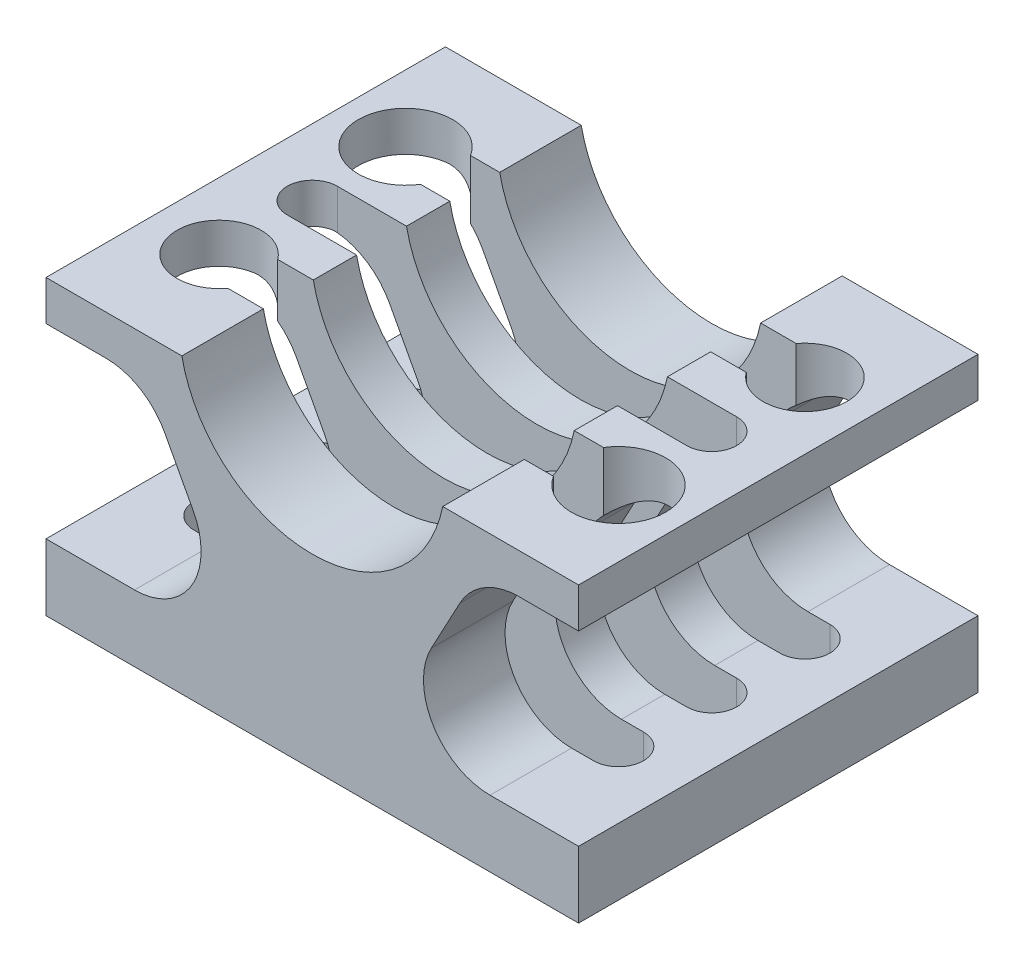
SolidWorks part; units mm, degrees
ref_plane "Front Plane" through (0, 0, 0) normal (0, 0, 1) x (1, 0, 0)
ref_plane "Top Plane" through (0, 0, 0) normal (0, 1, 0) x (1, 0, 0)
ref_plane "Right Plane" through (0, 0, 0) normal (1, 0, 0) x (0, 0, -1)
sketch "Sketch1" plane through (0, 0, 0) normal (0, 0, 1) x (1, 0, 0)
  line L0 (38.1, 30.48) -> (50.8, 30.48)
  line L1 (0, 0) -> (50.8, 0)
  line L2 (0, 0) -> (0, 6.35)
  line L3 (0, 30.48) -> (12.7, 30.48)
  line L4 (50.8, 0) -> (50.8, 6.35)
  line L5 (0, 24.13) -> (0, 30.48)
  line L6 (0, 24.13) -> (9.525, 24.13)
  line L8 (0, 6.35) -> (19.05, 6.35)
  line L9 (9.525, 24.13) -> (19.05, 6.35)
  line L10 (50.8, 24.13) -> (50.8, 30.48)
  line L11 (50.8, 24.13) -> (41.275, 24.13)
  line L13 (50.8, 6.35) -> (31.75, 6.35)
  line L14 (41.275, 24.13) -> (31.75, 6.35)
  arc A0 (12.7, 30.48) -> (38.1, 30.48) centre (25.4, 30.48) ccw
  dimension "D1" = 12.7
  dimension "D2" = 12.7
  dimension "D3" = 12.7
  dimension "D4" = 30.48
  dimension "D5" = 9.525
  dimension "D6" = 6.35
  dimension "D7" = 6.35
  dimension "D8" = 19.05
extrude "Boss-Extrude1" add sketch "Sketch1" along normal blind 38.1
sketch "Sketch3" plane through (0, 0, 0) normal (0, -1, 0) x (1, 0, 0)
  line L0 (6.35, 21.4313) -> (44.45, 21.4312)
  line L1 (6.35, 16.6687) -> (44.45, 16.6688)
  line L2 (0, 38.1) -> (0, 0) construction
  line L3 (6.35, 30.3213) -> (44.45, 30.3213)
  line L4 (6.35, 25.5587) -> (44.45, 25.5587)
  line L5 (6.35, 12.5413) -> (44.45, 12.5413)
  line L6 (6.35, 7.7787) -> (44.45, 7.7787)
  arc A0 (6.35, 21.4313) -> (6.35, 16.6687) centre (6.35, 19.05) ccw
  arc A1 (44.45, 16.6688) -> (44.45, 21.4312) centre (44.45, 19.05) ccw
  arc A2 (6.35, 30.3213) -> (6.35, 25.5587) centre (6.35, 27.94) ccw
  arc A3 (44.45, 25.5587) -> (44.45, 30.3213) centre (44.45, 27.94) ccw
  arc A4 (6.35, 12.5413) -> (6.35, 7.7787) centre (6.35, 10.16) ccw
  arc A5 (44.45, 7.7787) -> (44.45, 12.5413) centre (44.45, 10.16) ccw
  point P22 (0, 0)
  point P23 (0, 0)
  dimension "D1" = 2.3813
  dimension "D2" = 38.1
  dimension "D4" = 2.3813
  dimension "D7" = 2.3813
  dimension "D3" = 6.35
  dimension "D5" = 6.35
  dimension "D6" = 8.89
  dimension "D8" = 8.89
extrude "Cut-Extrude2" cut sketch "Sketch3" against normal through all
fillet "Fillet1" radius 6.35 16 edges at (41.275, 24.13, 3.8894) (41.275, 24.13, 34.2106) (19.05, 6.35, 34.2106) (19.05, 6.35, 23.495) (19.05, 6.35, 14.605) (19.05, 6.35, 3.8894) (31.75, 6.35, 34.2106) (31.75, 6.35, 23.495) (31.75, 6.35, 14.605) (31.75, 6.35, 3.8894) (9.525, 24.13, 34.2106) (9.525, 24.13, 23.495) (9.525, 24.13, 14.605) (9.525, 24.13, 3.8894) (41.275, 24.13, 23.495) (41.275, 24.13, 14.605)
sketch "Sketch4" plane through (0, 0, 38.1) normal (0, 0, 1) x (1, 0, 0)
  line L0 (50.8, 24.13) -> (50.8, 30.48) construction
  line L1 (0, 30.48) -> (50.8, 30.48)
  line L2 (0, 30.48) -> (0, 27.94)
  line L3 (0, 27.94) -> (50.8, 27.94)
  line L4 (50.8, 30.48) -> (50.8, 27.94)
  dimension "D1" = 2.54
extrude "Cut-Extrude3" cut sketch "Sketch4" against normal through all
sketch "Sketch5" plane through (0, 24.13, 0) normal (0, -1, 0) x (1, 0, 0)
  circle A1 centre (44.45, 27.94) radius 4.5
  circle A2 centre (6.35, 27.94) radius 4
  circle A3 centre (6.35, 10.16) radius 4.5
  circle A4 centre (44.45, 10.16) radius 4
  dimension "D1" = 8
  dimension "D3" = 9
extrude "Cut-Extrude5" cut sketch "Sketch5" against normal blind 25.4 and the other way blind 5.08
